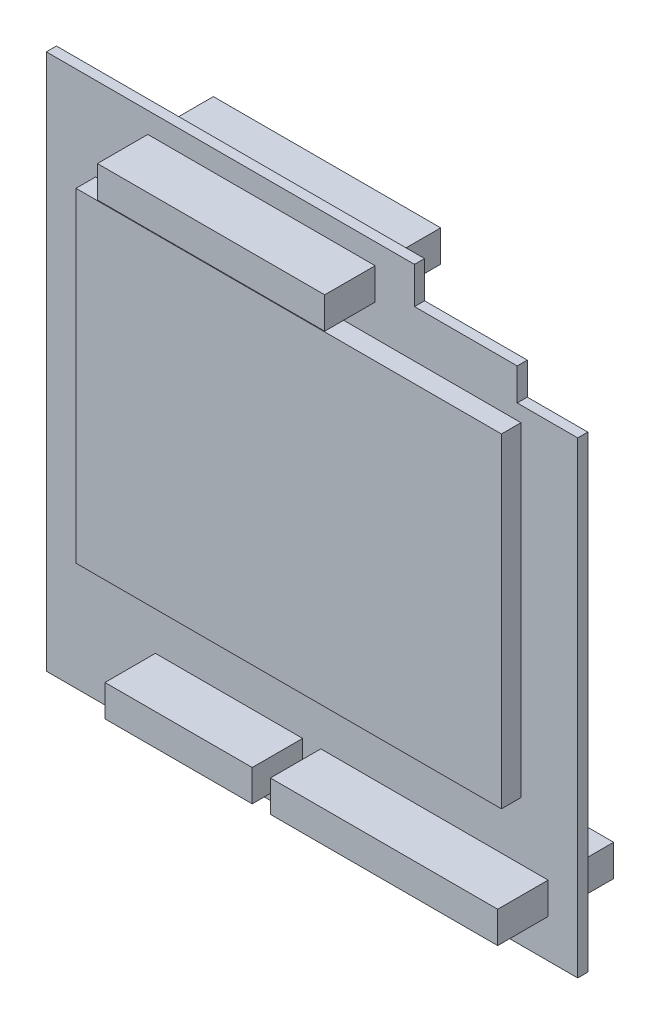
SolidWorks part; units mm, degrees
ref_plane "Front Plane" through (0, 0, 0) normal (0, 0, 1) x (1, 0, 0)
ref_plane "Top Plane" through (0, 0, 0) normal (0, 1, 0) x (1, 0, 0)
ref_plane "Right Plane" through (0, 0, 0) normal (1, 0, 0) x (0, 0, -1)
sketch "Sketch1" plane through (0, 0, 0) normal (0, 0, 1) x (1, 0, 0)
  line L0 (0, 0) -> (84.3, 0)
  line L1 (0, 0) -> (0, -85.09)
  line L2 (84.3, 0) -> (84.3, -85.09)
  line L3 (0, -85.09) -> (84.3, -85.09)
  dimension "D1" = 85.09
  dimension "D2" = 84.3
extrude "Boss-Extrude1" add sketch "Sketch1" along normal blind 1.6
sketch "Sketch2" plane through (0, 0, 1.6) normal (0, 0, 1) x (1, 0, 0)
  line L0 (7.8, -13.3) -> (75.3, -13.3)
  line L1 (7.8, -13.3) -> (7.8, -64.8)
  line L2 (75.3, -13.3) -> (75.3, -64.8)
  line L3 (7.8, -64.8) -> (75.3, -64.8)
  line L4 (84.3, 0) -> (0, 0) construction
  line L5 (0, 0) -> (0, -85.09) construction
  dimension "D1" = 51.5
  dimension "D2" = 67.5
  dimension "D3" = 13.3
  dimension "D4" = 7.8
extrude "Boss-Extrude2" add sketch "Sketch2" along normal blind 3.1
sketch "Sketch3" plane through (0, 0, 1.6) normal (0, 0, 1) x (1, 0, 0)
  line L0 (84.3, 0) -> (58.4, 0)
  line L1 (84.3, 0) -> (84.3, -10.89)
  line L2 (58.4, 0) -> (58.4, -5.8)
  line L3 (84.3, -10.89) -> (74.7, -10.89)
  line L4 (84.3, 0) -> (0, 0) construction
  line L5 (0, 0) -> (0, -85.09) construction
  line L6 (0, -85.09) -> (84.3, -85.09) construction
  line L7 (58.4, -5.8) -> (74.7, -5.8)
  line L9 (74.7, -5.8) -> (74.7, -10.89)
  point P14 (74.7, -8.345)
  dimension "D1" = 58.4
  dimension "D2" = 74.2
  dimension "D3" = 5.8
  dimension "D4" = 9.6
extrude "Cut-Extrude1" cut sketch "Sketch3" against normal through all
sketch "Sketch4" plane through (0, 0, 1.6) normal (0, 0, 1) x (1, 0, 0)
  line L0 (17.3, -73.99) -> (40.66, -73.99)
  line L1 (17.3, -73.99) -> (17.3, -78.99)
  line L2 (40.66, -73.99) -> (40.66, -78.99)
  line L3 (17.3, -78.99) -> (40.66, -78.99)
  line L4 (0, 0) -> (0, -85.09) construction
  line L5 (0, -85.09) -> (84.3, -85.09) construction
  line L6 (43.54, -73.99) -> (43.54, -78.99)
  line L7 (43.54, -73.99) -> (79.6, -73.99)
  line L8 (43.54, -78.99) -> (79.6, -78.99)
  line L9 (79.6, -73.99) -> (79.6, -78.99)
  line L10 (16.1, -3.3) -> (52.16, -3.3)
  line L11 (16.1, -3.3) -> (16.1, -8.3)
  line L12 (52.16, -3.3) -> (52.16, -8.3)
  line L13 (16.1, -8.3) -> (52.16, -8.3)
  line L14 (58.4, 0) -> (0, 0) construction
  line L15 (84.3, -85.09) -> (84.3, -10.89) construction
  point P0 (40.66, -76.49)
  dimension "D1" = 23.36
  dimension "D2" = 5
  dimension "D3" = 17.3
  dimension "D4" = 6.1
  dimension "D5" = 3.3
  dimension "D6" = 5
  dimension "D7" = 36.06
  dimension "D8" = 36.06
  dimension "D9" = 16.1
  dimension "D10" = 4.7
extrude "Boss-Extrude3" add sketch "Sketch4" along normal blind 8 and the other way blind 10.4
